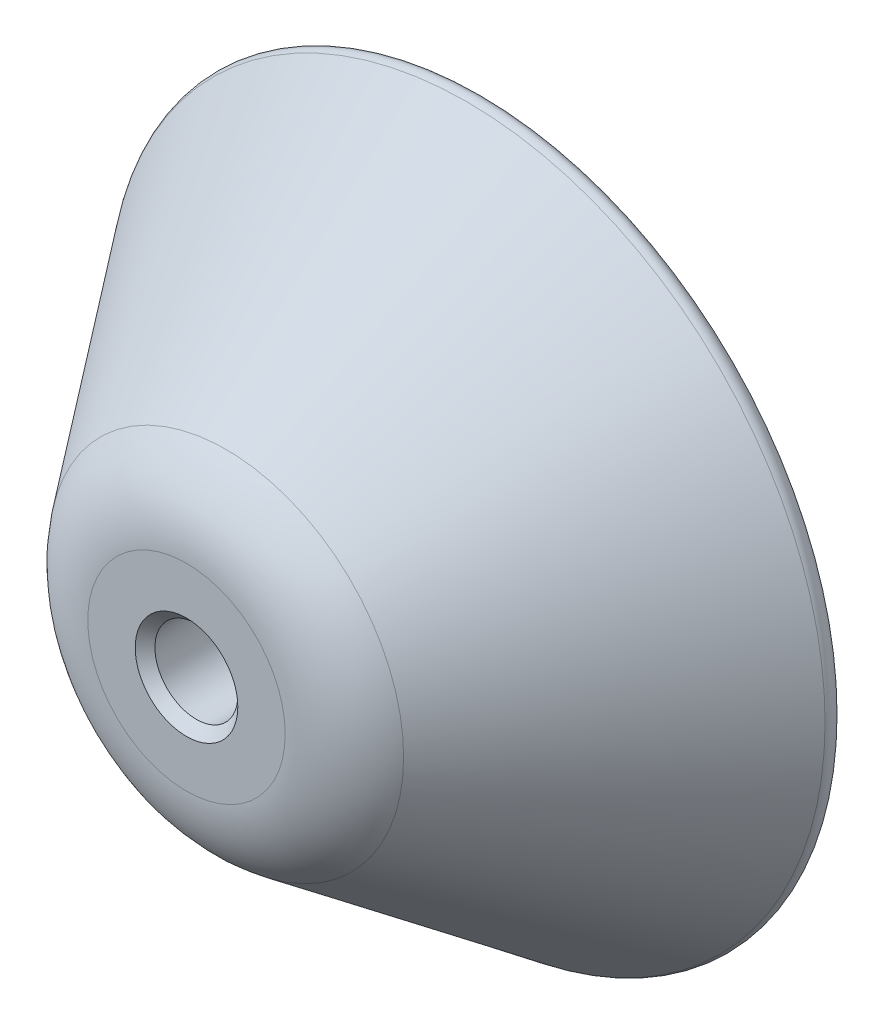
SolidWorks part; units mm, degrees
material "ABS"
ref_plane "Front Plane" through (0, 0, 0) normal (0, 0, 1) x (1, 0, 0)
ref_plane "Top Plane" through (0, 0, 0) normal (0, 1, 0) x (1, 0, 0)
ref_plane "Right Plane" through (0, 0, 0) normal (1, 0, 0) x (0, 0, -1)
sketch "Sketch1" plane through (0, 0, 0) normal (0, 1, 0) x (1, 0, 0)
  line L0 (-37.5, 0) -> (0, 0)
  line L1 (0, 0) -> (0, -30)
  line L2 (0, -30) -> (-15, -30)
  line L3 (-15, -30) -> (-37.5, 0)
  line L4 (0, 0) -> (0, -30) construction
  dimension "D1" = 37.5
  dimension "D2" = 15
  dimension "D3" = 30
revolve "Revolve1" add sketch "Sketch1" angle 360 about L4
fillet "Fillet1" radius 1 1 edges at (-37.5, 0, 0)
fillet "Fillet2" radius 10 1 edges at (-15, 0, 30)
sketch "Sketch2" plane through (0, 0, 30) normal (0, 0, 1) x (1, 0, 0)
  circle A0 centre (0, 0) radius 4.2
  dimension "D1" = 8.4
extrude "Cut-Extrude1" cut sketch "Sketch2" against normal through all
sketch "Sketch3" plane through (0, 0, 0) normal (0, 0, -1) x (-1, 0, 0)
  line L1 (-8.3, 0) -> (-4.15, -7.188)
  line L2 (-4.15, -7.188) -> (4.15, -7.188)
  line L3 (4.15, -7.188) -> (8.3, 0)
  line L4 (8.3, 0) -> (4.15, 7.188)
  line L5 (4.15, 7.188) -> (-4.15, 7.188)
  line L6 (-4.15, 7.188) -> (-8.3, 0)
  circle A0 centre (0, 0) radius 7.188 construction
  dimension "D1" = 14.376
extrude "Cut-Extrude2" cut sketch "Sketch3" along normal through all from offset 8 offset against normal yes
chamfer "Chamfer1" distance 1 angle 45 8 edges at (4.2, 0, 30) (-6.225, 3.594, 0) (-6.225, -3.594, 0) (0, -7.188, 0) (6.225, -3.594, 0) (6.225, 3.594, 0) (0, 7.188, 0) (-4.2, 0, 8)
